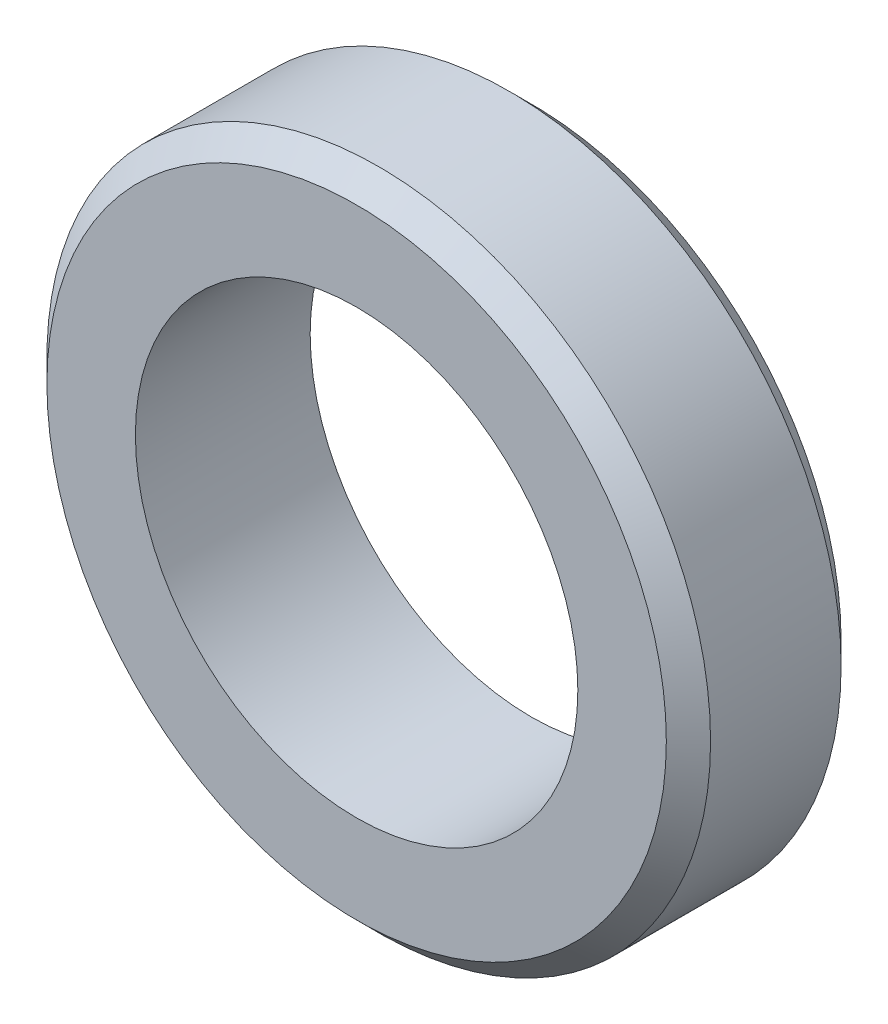
SolidWorks part; units mm, degrees
material "Plain Carbon Steel"
ref_plane "Front Plane" through (0, 0, 0) normal (0, 0, 1) x (1, 0, 0)
ref_plane "Top Plane" through (0, 0, 0) normal (0, 1, 0) x (1, 0, 0)
ref_plane "Right Plane" through (0, 0, 0) normal (1, 0, 0) x (0, 0, -1)
sketch "Sketch1" plane through (0, 0, 0) normal (0, 0, 1) x (1, 0, 0)
  circle A0 centre (0, 0) radius 19.05
  circle A1 centre (0, 0) radius 12.7
  dimension "D1" = 25.4
  dimension "D2" = 38.1
extrude "Boss-Extrude1" add sketch "Sketch1" along normal blind 10.033
chamfer "Chamfer1" distance 1.27 angle 45 2 edges at (19.05, 0, 0) (19.05, 0, 10.033)
